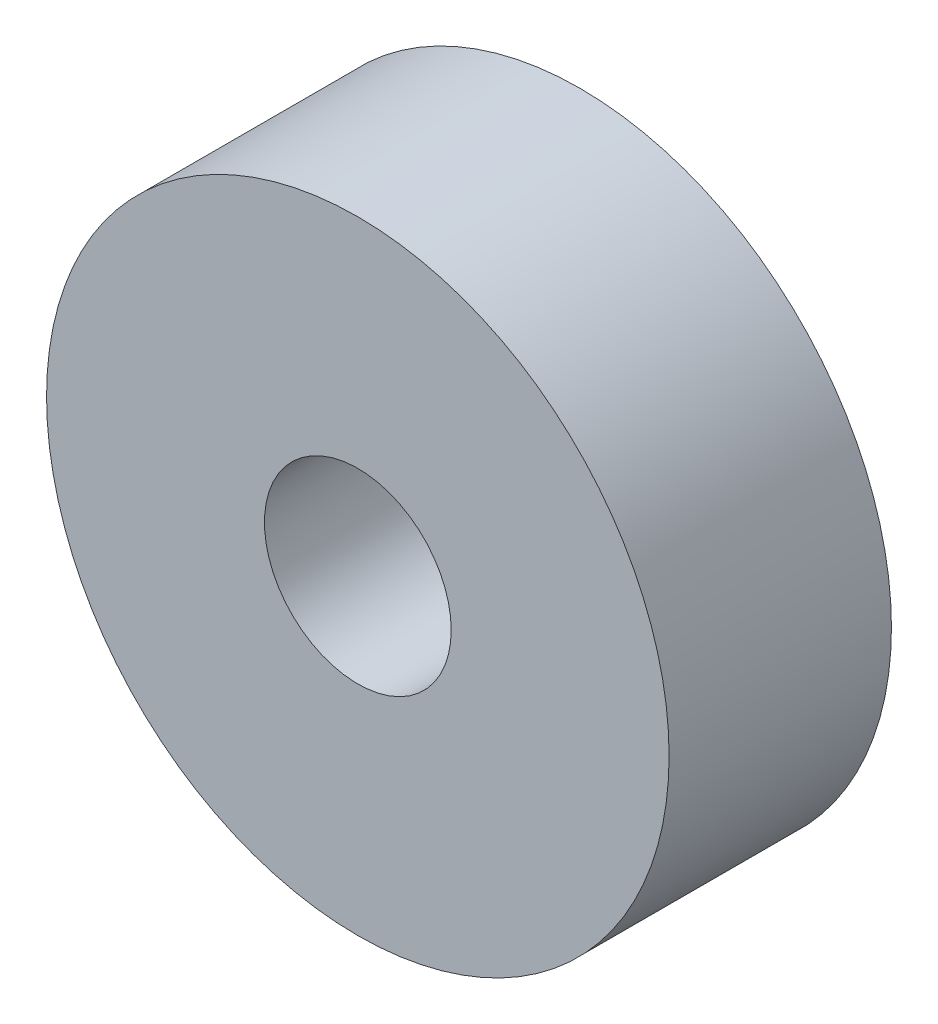
SolidWorks part; units mm, degrees
ref_plane "Front Plane" through (0, 0, 0) normal (0, 0, 1) x (1, 0, 0)
ref_plane "Top Plane" through (0, 0, 0) normal (0, 1, 0) x (1, 0, 0)
ref_plane "Right Plane" through (0, 0, 0) normal (1, 0, 0) x (0, 0, -1)
sketch "Sketch1" plane through (0, 0, 0) normal (0, 0, 1) x (1, 0, 0)
  circle A0 centre (0, 0) radius 7
  circle A1 centre (0, 0) radius 2.1
  dimension "D1" = 14
  dimension "D2" = 4.2
extrude "Boss-Extrude1" add sketch "Sketch1" along normal blind 5
